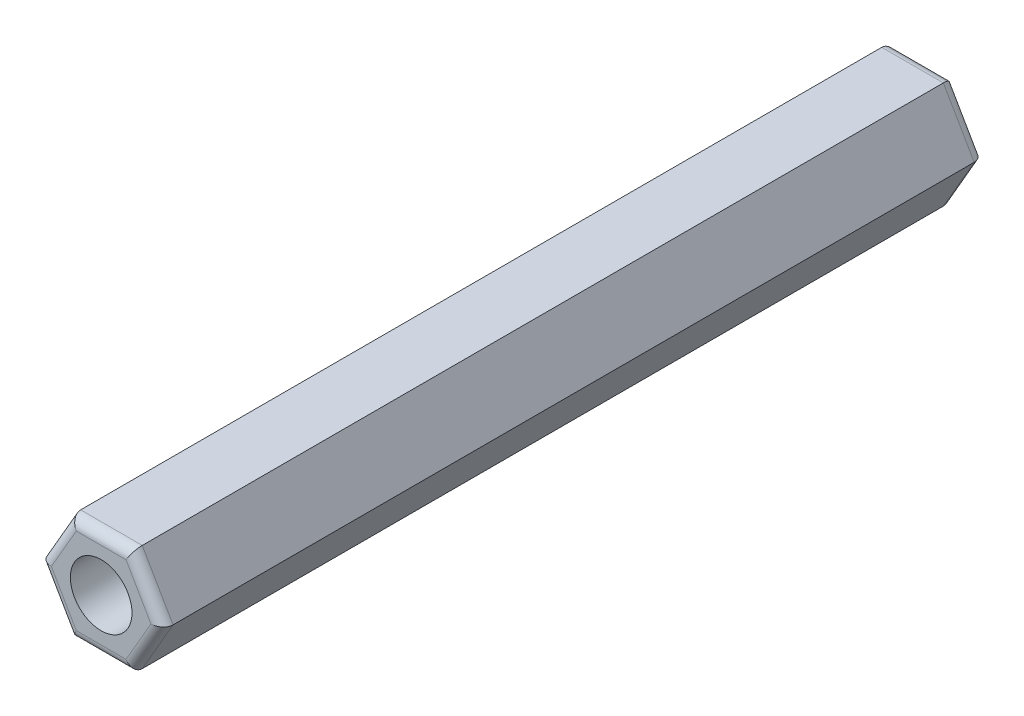
SolidWorks part; units mm, degrees
ref_plane "正面" through (0, 0, 0) normal (0, 0, 1) x (1, 0, 0)
ref_plane "平面" through (0, 0, 0) normal (0, 1, 0) x (1, 0, 0)
ref_plane "右側面" through (0, 0, 0) normal (1, 0, 0) x (0, 0, -1)
sketch "ｽｹｯﾁ1" plane through (0, 0, 0) normal (0, 0, 1) x (1, 0, 0)
  line L1 (3, 0) -> (1.5, 2.5981)
  line L2 (1.5, 2.5981) -> (-1.5, 2.5981)
  line L3 (-1.5, 2.5981) -> (-3, 0)
  line L4 (-3, 0) -> (-1.5, -2.5981)
  line L5 (-1.5, -2.5981) -> (1.5, -2.5981)
  line L6 (1.5, -2.5981) -> (3, 0)
  circle A0 centre (0, 0) radius 2.5981 construction
extrude "ﾎﾞｽ - 押し出し2" add sketch "ｽｹｯﾁ1" along normal blind 40
sketch "ｽｹｯﾁ2" plane through (0, 0, 40) normal (0, 0, 1) x (1, 0, 0)
  circle A0 centre (0, 0) radius 1.5
sketch "ｽｹｯﾁ3" plane through (0, 0, 0) normal (0, 0, -1) x (-1, 0, 0)
  circle A0 centre (0, 0) radius 1.75
extrude "ｶｯﾄ - 押し出し1" cut sketch "ｽｹｯﾁ3" against normal blind 5
fillet "ﾌｨﾚｯﾄ1" radius 0.5 12 edges at (-2.25, 1.299, 0) (0, 2.5981, 0) (2.25, 1.299, 0) (2.25, -1.299, 0) (-2.25, -1.299, 0) (0, -2.5981, 0) (2.25, -1.299, 40) (0, -2.5981, 40) (-2.25, -1.299, 40) (-2.25, 1.299, 40) (0, 2.5981, 40) (2.25, 1.299, 40)
extrude "ｶｯﾄ - 押し出し2" cut sketch "ｽｹｯﾁ2" against normal blind 5
